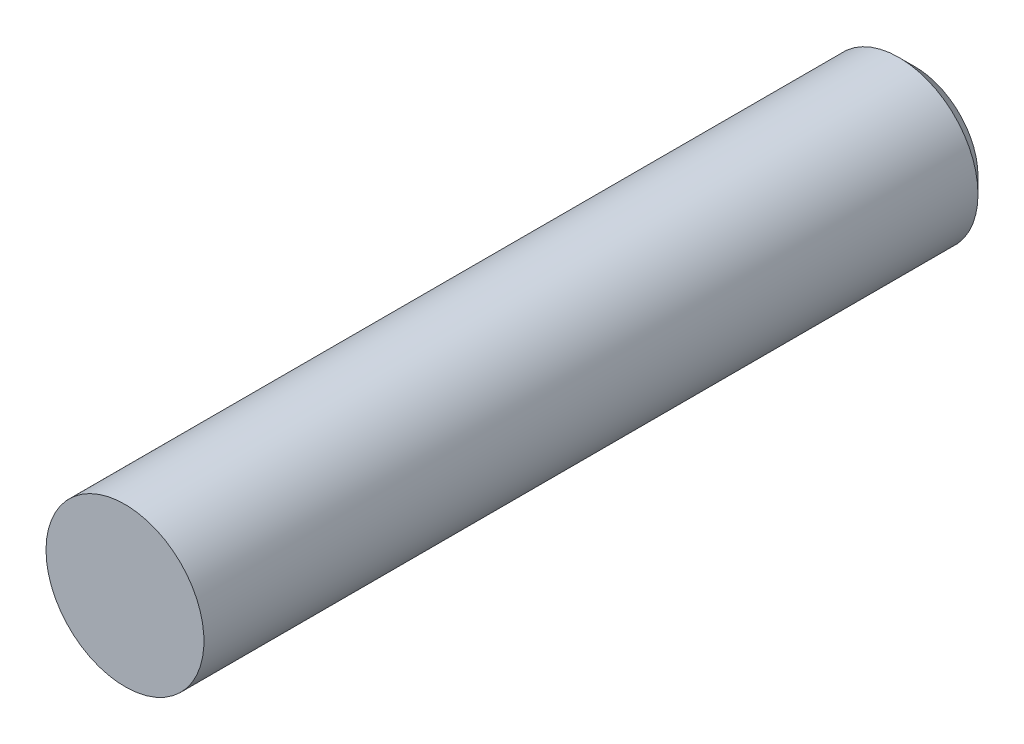
SolidWorks part; units mm, degrees
ref_plane "Front" through (0, 0, 0) normal (0, 0, 1) x (1, 0, 0)
ref_plane "Top" through (0, 0, 0) normal (0, 1, 0) x (1, 0, 0)
ref_plane "Right" through (0, 0, 0) normal (1, 0, 0) x (0, 0, -1)
sketch "Sketch1" plane through (0, 0, 0) normal (0, 0, 1) x (1, 0, 0)
  circle A0 centre (0, 0) radius 2.5
  dimension "dia" = 5
extrude "Extrude1" add sketch "Sketch1" along normal mid plane 200
sketch "Sketch2" plane through (0, 0, 0) normal (1, 0, 0) x (0, 0, -1)
  line L0 (100, 2.5) -> (-100, 2.5) construction
  point P0 (-100, 2.5)
  point P1 (100, 2.5)
  point P2 (-90, 2.5)
  point P5 (90, 2.5)
  dimension "D1" = 10
  dimension "D2" = 10
chamfer "Chamfer1" distance 0.5 angle 45 2 edges at (2.5, 0, -100) (2.5, 0, 100)
sketch "Sketch3" plane through (0, 0, 100) normal (0, 0, 1) x (1, 0, 0)
  line L1 (9.7712, 6.7183) -> (-9.7712, 6.7183)
  line L2 (9.7712, 6.7183) -> (9.7712, -6.7183)
  line L3 (9.7712, -6.7183) -> (-9.7712, -6.7183)
  line L4 (-9.7712, 6.7183) -> (-9.7712, -6.7183)
  line L5 (9.7712, 6.7183) -> (-9.7712, -6.7183) construction
  line L6 (9.7712, -6.7183) -> (-9.7712, 6.7183) construction
  point P0 (0, 0)
extrude "Cut-Extrude1" cut sketch "Sketch3" against normal blind 175
equation "\"D1@Chamfer1\" = \"dia@Sketch1\" * .1"
equation "\"D1@Sketch2\"=\"dia@sketch1\"*2"
equation "\"D2@Sketch2\"=\"D1@Sketch2\""
